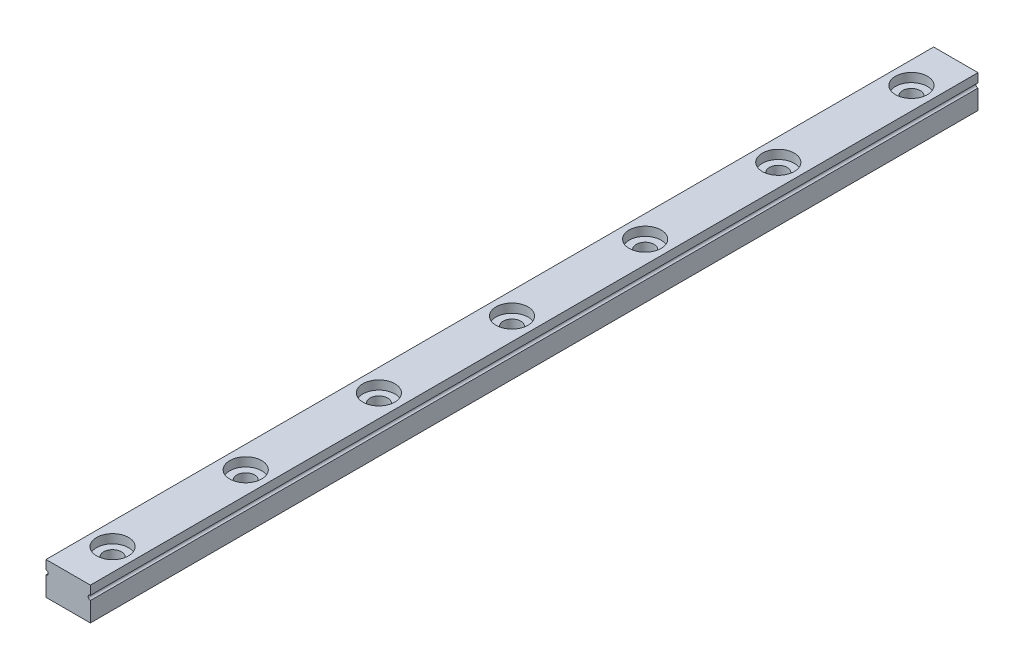
SolidWorks part; units mm, degrees
ref_plane "Front Plane" through (0, 0, 0) normal (0, 0, 1) x (1, 0, 0)
ref_plane "Top Plane" through (0, 0, 0) normal (0, 1, 0) x (1, 0, 0)
ref_plane "Right Plane" through (0, 0, 0) normal (1, 0, 0) x (0, 0, -1)
sketch "Sketch1" plane through (0, 0, 0) normal (0, 0, 1) x (1, 0, 0)
  line L0 (0, 15.8245) -> (0, -6.7102) construction
  line L13 (-2.5, 3.7) -> (2.5, 3.7)
  line L14 (2.5, 3.7) -> (2.5, 2.7)
  line L15 (2.5, 0) -> (-2.5, 0)
  line L16 (2.5, 2.7) -> (0, 2.7) construction
  line L17 (2.5, 2.2) -> (2.5, 0)
  line L18 (-2.5, 2.2) -> (-2.5, 0)
  line L19 (-2.5, 3.7) -> (-2.5, 2.7)
  arc A0 (2.5, 2.7) -> (2.5, 2.2) centre (2.5, 2.45) ccw
  arc A1 (-2.5, 2.7) -> (-2.5, 2.2) centre (-2.5, 2.45) cw
  point P14 (0, 0)
  point P15 (0, 3.7)
  dimension "D3" = 1
  dimension "D4" = 0.5
  dimension "D1" = 2.5
  dimension "D2" = 3.7
extrude "Boss-Extrude1" add sketch "Sketch1" along normal mid plane 100
sketch "Sketch2" plane through (0, 3.7, 0) normal (0, 1, 0) x (1, 0, 0)
  circle A0 centre (0, 0) radius 1.8
  dimension "D1" = 3.6
extrude "Cut-Extrude1" cut sketch "Sketch2" against normal blind 1
sketch "Sketch3" plane through (0, 3.7, 0) normal (0, 1, 0) x (1, 0, 0)
  circle A0 centre (0, 0) radius 1
  dimension "D1" = 2
extrude "Cut-Extrude3" cut sketch "Sketch3" against normal through all
pattern_linear "LPattern1" count 7 spacing 15 along (0, 0, -1) of "Cut-Extrude1", "Cut-Extrude3"
pattern_linear "LPattern2" count 7 spacing 15 along (0, 0, 1) of "Cut-Extrude1", "Cut-Extrude3"
